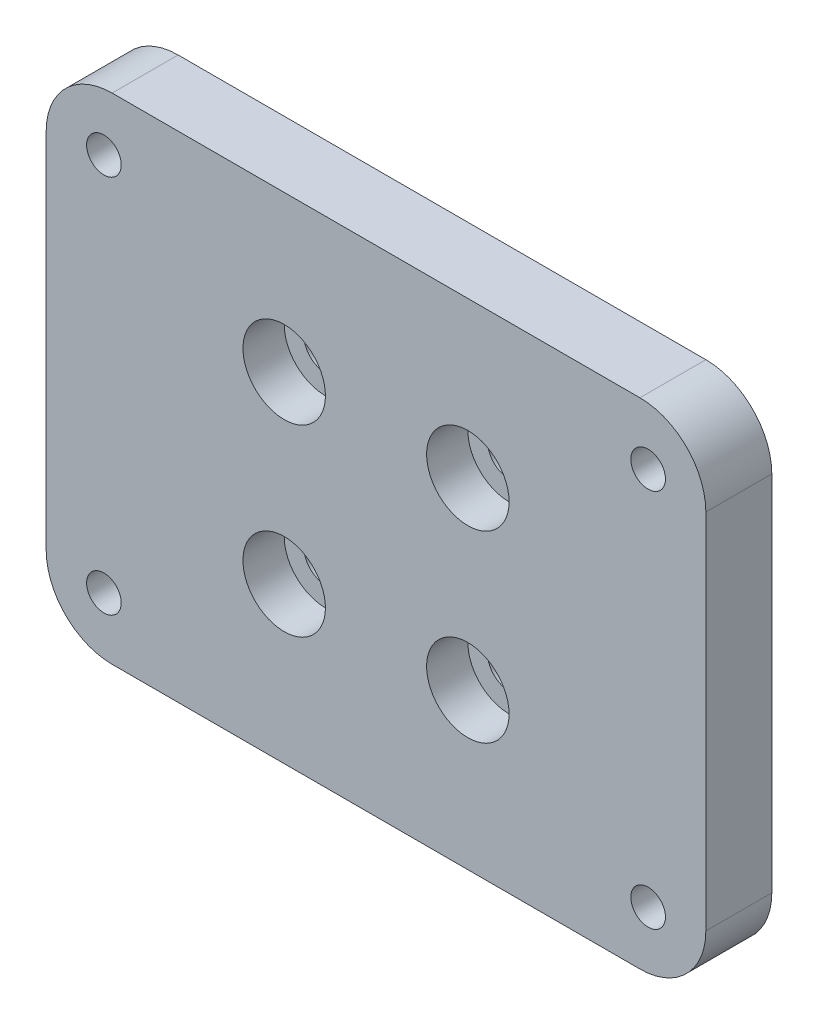
SolidWorks part; units mm, degrees
ref_plane "正面" through (0, 0, 0) normal (0, 0, 1) x (1, 0, 0)
ref_plane "平面" through (0, 0, 0) normal (0, 1, 0) x (1, 0, 0)
ref_plane "右側面" through (0, 0, 0) normal (1, 0, 0) x (0, 0, -1)
sketch "ｽｹｯﾁ1" plane through (0, 0, 0) normal (0, 0, 1) x (1, 0, 0)
  line L1 (0, 0) -> (80, 0)
  line L2 (0, 0) -> (0, 60)
  line L3 (0, 60) -> (80, 60)
  line L4 (80, 0) -> (80, 60)
  dimension "D1" = 60
  dimension "D2" = 80
extrude "ﾎﾞｽ - 押し出し1" add sketch "ｽｹｯﾁ1" along normal blind 8
sketch "ｽｹｯﾁ2" plane through (0, 0, 8) normal (0, 0, 1) x (1, 0, 0)
  line L0 (27.0246, 42.9754) -> (30.7015, 39.2985)
  line L1 (24.25, 14.25) -> (55.75, 14.25)
  line L2 (24.25, 14.25) -> (24.25, 45.75)
  line L3 (24.25, 45.75) -> (55.75, 45.75)
  line L4 (55.75, 14.25) -> (55.75, 45.75)
  line L5 (30.7015, 20.7015) -> (27.0246, 17.0246)
  line L6 (52.9754, 42.9754) -> (49.2985, 39.2985)
  line L7 (49.2985, 20.7015) -> (52.9754, 17.0246)
  circle A0 centre (40, 30) radius 15.75
  circle A1 centre (28.8631, 41.1369) radius 2.6
  circle A2 centre (51.1369, 41.1369) radius 2.6
  circle A3 centre (51.1369, 18.8631) radius 2.6
  circle A4 centre (28.8631, 18.8631) radius 2.6
  dimension "D1" = 4
extrude "ｶｯﾄ - 押し出し1" cut sketch "ｽｹｯﾁ2" against normal blind 10
fillet "ﾌｨﾚｯﾄ1" radius 8 4 edges at (0, 0, 4) (80, 0, 4) (80, 60, 4) (0, 60, 4)
sketch "ｽｹｯﾁ3" plane through (0, 0, 8) normal (0, 0, 1) x (1, 0, 0)
  circle A0 centre (28.8631, 41.1369) radius 5
  circle A1 centre (51.1369, 41.1369) radius 5
  circle A2 centre (28.8631, 18.8631) radius 5
  circle A3 centre (51.1369, 18.8631) radius 5
  dimension "D1" = 10
  dimension "D2" = 10
  dimension "D3" = 10
  dimension "D4" = 10
extrude "ｶｯﾄ - 押し出し2" cut sketch "ｽｹｯﾁ3" against normal blind 5
sketch "ｽｹｯﾁ5" plane through (0, 0, 8) normal (0, 0, 1) x (1, 0, 0)
  line L0 (0, 52) -> (0, 8) construction
  line L1 (73, 7) -> (7, 7)
  line L2 (73, 7) -> (73, 53)
  line L3 (73, 53) -> (7, 53)
  line L4 (7, 7) -> (7, 53)
  line L5 (72, 60) -> (8, 60) construction
  line L6 (8, 0) -> (72, 0) construction
  line L7 (80, 8) -> (80, 52) construction
  circle A0 centre (7, 53) radius 2.1
  circle A1 centre (73, 53) radius 2.1
  circle A2 centre (73, 7) radius 2.1
  circle A3 centre (7, 7) radius 2.1
  dimension "D5" = 4.2
  dimension "D6" = 4.2
  dimension "D7" = 4.2
  dimension "D8" = 4.2
  dimension "D1" = 7
  dimension "D2" = 7
  dimension "D3" = 7
  dimension "D4" = 7
extrude "ｶｯﾄ - 押し出し4" cut sketch "ｽｹｯﾁ5" against normal blind 10 contours A0 | A1 | A2 | A3
